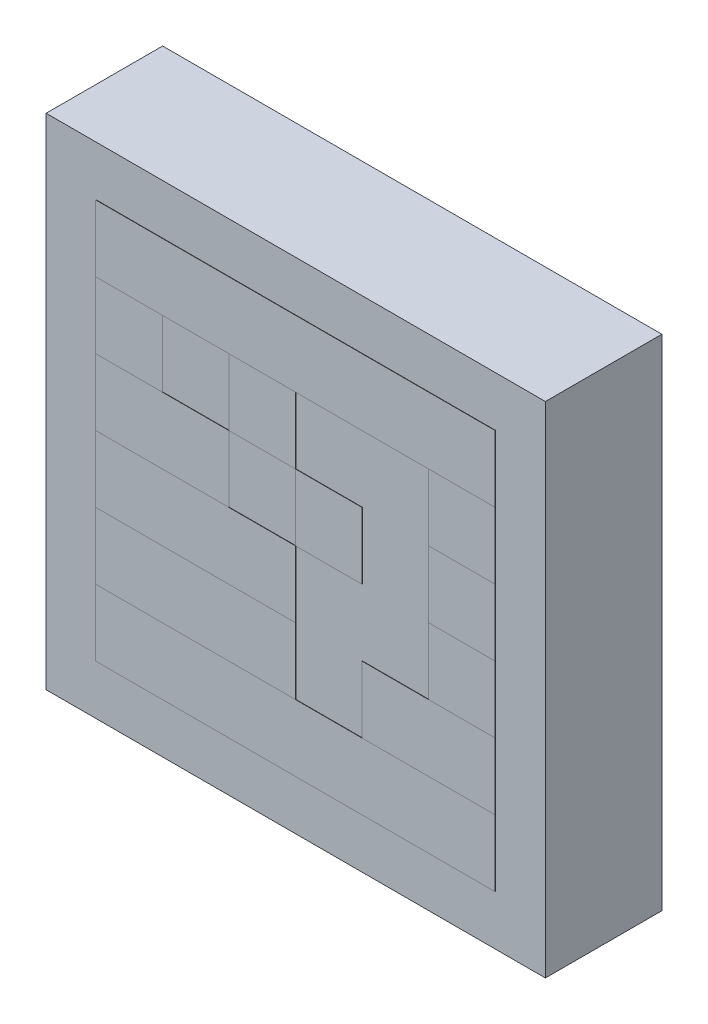
SolidWorks part; units mm, degrees
ref_plane "前视基准面" through (0, 0, 0) normal (0, 0, 1) x (1, 0, 0)
ref_plane "上视基准面" through (0, 0, 0) normal (0, 1, 0) x (1, 0, 0)
ref_plane "右视基准面" through (0, 0, 0) normal (1, 0, 0) x (0, 0, -1)
other "Configuration Table"
sketch "草图1" plane through (0, 0, 0) normal (0, 0, 1) x (1, 0, 0)
  line L1 (-30, -30) -> (30, -30)
  line L2 (-30, -30) -> (-30, 30)
  line L3 (-30, 30) -> (30, 30)
  line L4 (30, -30) -> (30, 30)
  dimension "D1" = 30
  dimension "D2" = 30
  dimension "D3" = 30
extrude "Coplanar_support60x60x14" add sketch "草图1" against normal blind 14
sketch "草图2" plane through (0, 0, 0) normal (0, 0, 1) x (1, 0, 0)
  line L1 (-24, 16) -> (24, 16)
  line L2 (-24, 16) -> (-24, 24)
  line L3 (-24, 24) -> (24, 24)
  line L4 (24, 16) -> (24, 24)
extrude "ID0_row0" add sketch "草图2" along normal blind 0.04 separate body
sketch "草图3" plane through (0, 0, 0) normal (0, 0, 1) x (1, 0, 0)
  line L1 (-24, 8) -> (-16, 8)
  line L2 (-24, 8) -> (-24, 16)
  line L3 (-24, 16) -> (-16, 16)
  line L4 (-16, 8) -> (-16, 16)
  line L6 (-8, 8) -> (0, 8)
  line L7 (-8, 8) -> (-8, 16)
  line L8 (-8, 16) -> (0, 16)
  line L9 (0, 8) -> (0, 16)
  line L11 (16, 8) -> (24, 8)
  line L12 (16, 8) -> (16, 16)
  line L13 (16, 16) -> (24, 16)
  line L14 (24, 8) -> (24, 16)
extrude "ID0_row1" add sketch "草图3" along normal blind 0.04 separate body
sketch "草图4" plane through (0, 0, 0) normal (0, 0, 1) x (1, 0, 0)
  line L1 (-24, 0) -> (-8, 0)
  line L2 (-24, 0) -> (-24, 8)
  line L3 (-24, 8) -> (-8, 8)
  line L4 (-8, 0) -> (-8, 8)
  line L6 (0, 0) -> (8, 0)
  line L7 (0, 0) -> (0, 8)
  line L8 (0, 8) -> (8, 8)
  line L9 (8, 0) -> (8, 8)
  line L11 (16, 0) -> (24, 0)
  line L12 (16, 0) -> (16, 8)
  line L13 (16, 8) -> (24, 8)
  line L14 (24, 0) -> (24, 8)
extrude "ID0_row2" add sketch "草图4" along normal blind 0.04 separate body
sketch "草图5" plane through (0, 0, 0) normal (0, 0, 1) x (1, 0, 0)
  line L1 (-24, -8) -> (0, -8)
  line L2 (-24, -8) -> (-24, 0)
  line L3 (-24, 0) -> (0, 0)
  line L4 (0, -8) -> (0, 0)
  line L6 (16, -8) -> (24, -8)
  line L7 (16, -8) -> (16, 0)
  line L8 (16, 0) -> (24, 0)
  line L9 (24, -8) -> (24, 0)
extrude "ID0_row3" add sketch "草图5" along normal blind 0.04 separate body
sketch "草图6" plane through (0, 0, 0) normal (0, 0, 1) x (1, 0, 0)
  line L1 (-24, -16) -> (0, -16)
  line L2 (-24, -16) -> (-24, -8)
  line L3 (-24, -8) -> (0, -8)
  line L4 (0, -16) -> (0, -8)
  line L6 (8, -16) -> (24, -16)
  line L7 (8, -16) -> (8, -8)
  line L8 (8, -8) -> (24, -8)
  line L9 (24, -16) -> (24, -8)
extrude "ID0_row4" add sketch "草图6" along normal blind 0.04 separate body
sketch "草图7" plane through (0, 0, 0) normal (0, 0, 1) x (1, 0, 0)
  line L1 (-24, -24) -> (24, -24)
  line L2 (-24, -24) -> (-24, -16)
  line L3 (-24, -16) -> (24, -16)
  line L4 (24, -24) -> (24, -16)
extrude "ID0_row5" add sketch "草图7" along normal blind 0.04 separate body
